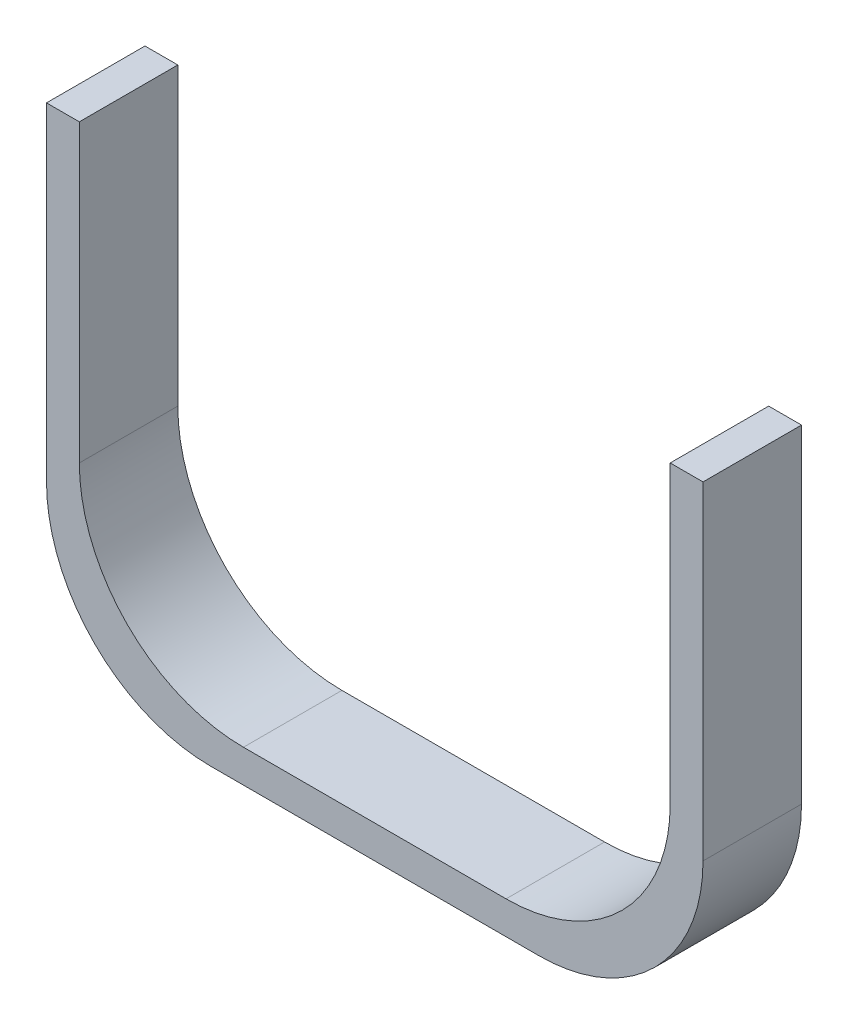
SolidWorks part; units mm, degrees
ref_plane "Front Plane" through (0, 0, 0) normal (0, 0, 1) x (1, 0, 0)
ref_plane "Top Plane" through (0, 0, 0) normal (0, 1, 0) x (1, 0, 0)
ref_plane "Right Plane" through (0, 0, 0) normal (1, 0, 0) x (0, 0, -1)
sketch "Sketch1" plane through (0, 0, 0) normal (0, 0, 1) x (1, 0, 0)
  line L0 (0, 0) -> (200, 0)
  line L1 (200, 0) -> (200, 150)
  line L2 (200, 150) -> (190, 150)
  line L3 (190, 150) -> (190, 10)
  line L4 (190, 10) -> (10, 10)
  line L5 (10, 10) -> (10, 150)
  line L6 (10, 150) -> (0, 150)
  line L7 (0, 150) -> (0, 0)
  dimension "D1" = 200
  dimension "D2" = 150
  dimension "D3" = 150
  dimension "D4" = 10
  dimension "D5" = 10
  dimension "D6" = 10
extrude "Boss-Extrude1" add sketch "Sketch1" along normal blind 30
fillet "Fillet1" radius 50 2 edges at (190, 10, 15) (10, 10, 15)
fillet "Fillet2" radius 50 2 edges at (200, 0, 15) (0, 0, 15)
